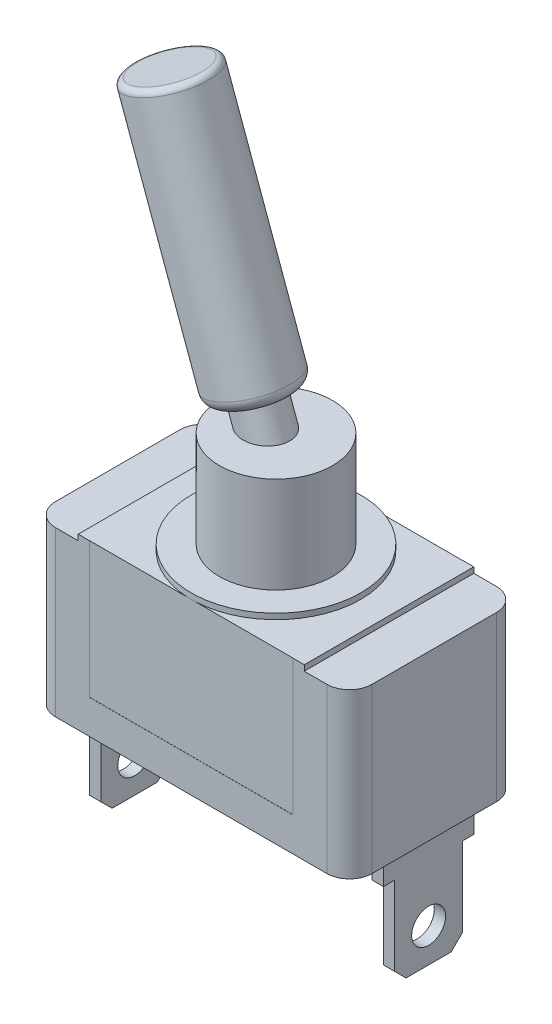
SolidWorks part; units mm, degrees
material "炭素鋼(普通)"
ref_plane "正面" through (0, 0, 0) normal (0, 0, 1) x (1, 0, 0)
ref_plane "平面" through (0, 0, 0) normal (0, 1, 0) x (1, 0, 0)
ref_plane "右側面" through (0, 0, 0) normal (1, 0, 0) x (0, 0, -1)
sketch "ｽｹｯﾁ1" plane through (0, 0, 0) normal (0, 0, 1) x (1, 0, 0)
  line L1 (14, -7.5) -> (-14, -7.5)
  line L2 (14, -7.5) -> (14, 7.5)
  line L3 (14, 7.5) -> (-14, 7.5)
  line L4 (-14, -7.5) -> (-14, 7.5)
  line L5 (14, -7.5) -> (-14, 7.5) construction
  line L6 (14, 7.5) -> (-14, -7.5) construction
  point P0 (0, 0)
  dimension "D1" = 15
  dimension "D2" = 28
extrude "ﾎﾞｽ - 押し出し1" add sketch "ｽｹｯﾁ1" along normal blind 15
sketch "ｽｹｯﾁ2" plane through (0, -7.5, 0) normal (0, -1, 0) x (1, 0, 0)
  line L0 (-14, 15) -> (14, 15) construction
  line L1 (-13.5, 11.5) -> (-12.5, 11.5)
  line L2 (-13.5, 11.5) -> (-13.5, 3.5)
  line L3 (-13.5, 3.5) -> (-12.5, 3.5)
  line L4 (-12.5, 11.5) -> (-12.5, 3.5)
  line L5 (-13.5, 11.5) -> (-12.5, 3.5) construction
  line L6 (-13.5, 3.5) -> (-12.5, 11.5) construction
  line L7 (12.5, 11.5) -> (13.5, 11.5)
  line L8 (12.5, 11.5) -> (12.5, 3.5)
  line L9 (12.5, 3.5) -> (13.5, 3.5)
  line L10 (13.5, 11.5) -> (13.5, 3.5)
  line L11 (12.5, 11.5) -> (13.5, 3.5) construction
  line L12 (12.5, 3.5) -> (13.5, 11.5) construction
  line L13 (-14, 0) -> (14, 0) construction
  line L14 (14, 15) -> (14, 0) construction
  line L15 (-14, 15) -> (-14, 0) construction
  point P0 (-13, 7.5)
  point P5 (13, 7.5)
  dimension "D1" = 3.5
  dimension "D2" = 3.5
  dimension "D3" = 0.5
  dimension "D4" = 1
  dimension "D5" = 0.5
  dimension "D6" = 3.5
  dimension "D7" = 3.5
  dimension "D8" = 1
extrude "ﾎﾞｽ - 押し出し2" add sketch "ｽｹｯﾁ2" along normal blind 2
sketch "ｽｹｯﾁ3" plane through (0, -9.5, 0) normal (0, -1, 0) x (1, 0, 0)
  line L0 (-12.5, 11.5) -> (-13.5, 11.5) construction
  line L1 (-13.5, 10.5) -> (-12.5, 10.5)
  line L2 (-13.5, 10.5) -> (-13.5, 4.5)
  line L3 (-13.5, 4.5) -> (-12.5, 4.5)
  line L4 (-12.5, 10.5) -> (-12.5, 4.5)
  line L5 (-13.5, 10.5) -> (-12.5, 4.5) construction
  line L6 (-13.5, 4.5) -> (-12.5, 10.5) construction
  line L7 (-13.5, 3.5) -> (-12.5, 3.5) construction
  line L8 (-13.5, 11.5) -> (-13.5, 3.5) construction
  line L9 (-12.5, 3.5) -> (-12.5, 11.5) construction
  point P0 (-13, 7.5)
  dimension "D1" = 1
  dimension "D2" = 1
extrude "ﾎﾞｽ - 押し出し3" add sketch "ｽｹｯﾁ3" along normal blind 8
sketch "ｽｹｯﾁ4" plane through (0, -9.5, 0) normal (0, -1, 0) x (1, 0, 0)
  line L0 (12.5, 11.5) -> (12.5, 3.5) construction
  line L1 (12.5, 10.5) -> (13.5, 10.5)
  line L2 (12.5, 10.5) -> (12.5, 4.5)
  line L3 (12.5, 4.5) -> (13.5, 4.5)
  line L4 (13.5, 10.5) -> (13.5, 4.5)
  line L5 (12.5, 10.5) -> (13.5, 4.5) construction
  line L6 (12.5, 4.5) -> (13.5, 10.5) construction
  line L7 (13.5, 3.5) -> (13.5, 11.5) construction
  line L8 (13.5, 11.5) -> (12.5, 11.5) construction
  line L9 (12.5, 3.5) -> (13.5, 3.5) construction
  point P0 (13, 7.5)
  dimension "D1" = 1
  dimension "D2" = 1
extrude "ﾎﾞｽ - 押し出し4" add sketch "ｽｹｯﾁ4" along normal blind 8
fillet "ﾌｨﾚｯﾄ1" radius 2 4 edges at (-14, 0, 0) (14, 0, 0) (14, 0, 15) (-14, 0, 15)
chamfer "面取り1" distance 1 angle 45 4 edges at (-13, -17.5, 4.5) (-13, -17.5, 10.5) (13, -17.5, 4.5) (13, -17.5, 10.5)
sketch "ｽｹｯﾁ5" plane through (13.5, 0, 0) normal (1, 0, 0) x (0, 0, -1)
  line L0 (-10.5, -16.5) -> (-10.5, -9.5) construction
  line L2 (-5.5, -17.5) -> (-9.5, -17.5) construction
  circle A0 centre (-7.5, -14.5) radius 1.5
  dimension "D1" = 3
  dimension "D2" = 3
  dimension "D3" = 3
extrude "ｶｯﾄ - 押し出し1" cut sketch "ｽｹｯﾁ5" against normal through all
sketch "ｽｹｯﾁ6" plane through (0, 7.5, 0) normal (0, 1, 0) x (1, 0, 0)
  line L0 (-14, -13) -> (-14, -2) construction
  line L1 (-14, 0) -> (-10, 0)
  line L2 (-14, 0) -> (-14, -15)
  line L3 (-14, -15) -> (-10, -15)
  line L4 (-10, 0) -> (-10, -15)
  line L5 (14, -13) -> (14, -2) construction
  line L6 (14, 0) -> (10, 0)
  line L7 (14, 0) -> (14, -15)
  line L8 (14, -15) -> (10, -15)
  line L9 (10, 0) -> (10, -15)
  line L10 (12, 0) -> (-12, 0) construction
  line L11 (12, -15) -> (-12, -15) construction
  dimension "D1" = 4
  dimension "D2" = 4
extrude "ｶｯﾄ - 押し出し2" cut sketch "ｽｹｯﾁ6" against normal blind 0.5
sketch "ｽｹｯﾁ7" plane through (0, 0, 15) normal (0, 0, 1) x (1, 0, 0)
  line L0 (0, 7.5) -> (0, -7.5) construction
  line L1 (10, 7.5) -> (-10, 7.5) construction
  line L2 (-12, -7.5) -> (12, -7.5) construction
  line L4 (-9, 7.5) -> (9, 7.5)
  line L5 (-9, 7.5) -> (-9, -4.5)
  line L6 (-9, -4.5) -> (9, -4.5)
  line L7 (9, 7.5) -> (9, -4.5)
  dimension "D1" = 12
  dimension "D2" = 9
  dimension "D3" = 9
extrude "ｶｯﾄ - 押し出し3" cut sketch "ｽｹｯﾁ7" against normal blind 0.01
sketch "ｽｹｯﾁ8" plane through (0, 0, 0) normal (0, 0, -1) x (-1, 0, 0)
  line L0 (0, 7.5) -> (0, -7.5) construction
  line L1 (-10, 7.5) -> (10, 7.5) construction
  line L2 (12, -7.5) -> (-12, -7.5) construction
  line L4 (-9, 7.5) -> (9, 7.5)
  line L5 (-9, 7.5) -> (-9, -4.5)
  line L6 (-9, -4.5) -> (9, -4.5)
  line L7 (9, 7.5) -> (9, -4.5)
  dimension "D1" = 12
  dimension "D2" = 9
  dimension "D3" = 9
extrude "ｶｯﾄ - 押し出し4" cut sketch "ｽｹｯﾁ8" against normal blind 0.01
sketch "ｽｹｯﾁ9" plane through (0, 7.5, 0) normal (0, 1, 0) x (1, 0, 0)
  line L0 (0, -14.99) -> (0, -0.01) construction
  line L1 (9, -14.99) -> (-9, -14.99) construction
  line L2 (-9, -0.01) -> (9, -0.01) construction
  line L3 (-10, -7.5) -> (10, -7.5) construction
  line L4 (-10, -15) -> (-10, 0) construction
  line L5 (10, 0) -> (10, -15) construction
  circle A0 centre (0, -7.5) radius 7.5
  dimension "D1" = 15
extrude "ﾎﾞｽ - 押し出し5" add sketch "ｽｹｯﾁ9" along normal blind 0.5
sketch "ｽｹｯﾁ10" plane through (0, 8, 0) normal (0, 1, 0) x (1, 0, 0)
  circle A0 centre (0, -7.5) radius 5
  dimension "D1" = 10
extrude "ﾎﾞｽ - 押し出し6" add sketch "ｽｹｯﾁ10" along normal blind 8.5
sketch "ｽｹｯﾁ20" plane through (0, 16.5, 0) normal (0, 1, 0) x (1, 0, 0)
  line L0 (0, -2.5) -> (0, -12.5) construction
  line L1 (-5, -7.5) -> (5, -7.5) construction
  circle A0 centre (0, -7.5) radius 5 construction
ref_plane "平面5" through (0, 0, 7.5) normal (0, 0, 1) x (1, 0, 0)
sketch "ｽｹｯﾁ21" plane through (0, 0, 7.5) normal (0, 0, 1) x (1, 0, 0)
  line L0 (-5, 16.5) -> (-5, 17.5) construction
  line L1 (-5, 17.5) -> (1.5778, 19.8941) construction
  line L2 (-1.7111, 18.6971) -> (-0.9114, 16.5) construction
  line L3 (-5, 16.5) -> (5, 16.5) construction
  dimension "D1" = 1
  dimension "D2" = 7
ref_plane "平面6" through (-6.2093, 17.0599, 0) normal (0.342, -0.9397, 0) x (-0.9397, -0.342, 0)
sketch "ｽｹｯﾁ22" plane through (-6.2093, 17.0599, 0) normal (0.342, -0.9397, 0) x (-0.9397, -0.342, 0)
  circle A0 centre (-4.7869, -7.5) radius 2
  dimension "D1" = 4
extrude "ﾎﾞｽ - 押し出し7" add sketch "ｽｹｯﾁ22" along normal up to next separate body
sketch "ｽｹｯﾁ23" plane through (-6.2093, 17.0599, 0) normal (0.342, -0.9397, 0) x (-0.9397, -0.342, 0)
  circle A0 centre (-4.7869, -7.5) radius 3.5
  dimension "D1" = 7
extrude "ﾎﾞｽ - 押し出し8" add sketch "ｽｹｯﾁ23" against normal blind 22.5
fillet "ﾌｨﾚｯﾄ2" radius 1 1 edges at (1.5778, 19.8941, 7.5)
fillet "ﾌｨﾚｯﾄ3" radius 0.5 1 edges at (-6.1176, 41.0372, 7.5)
